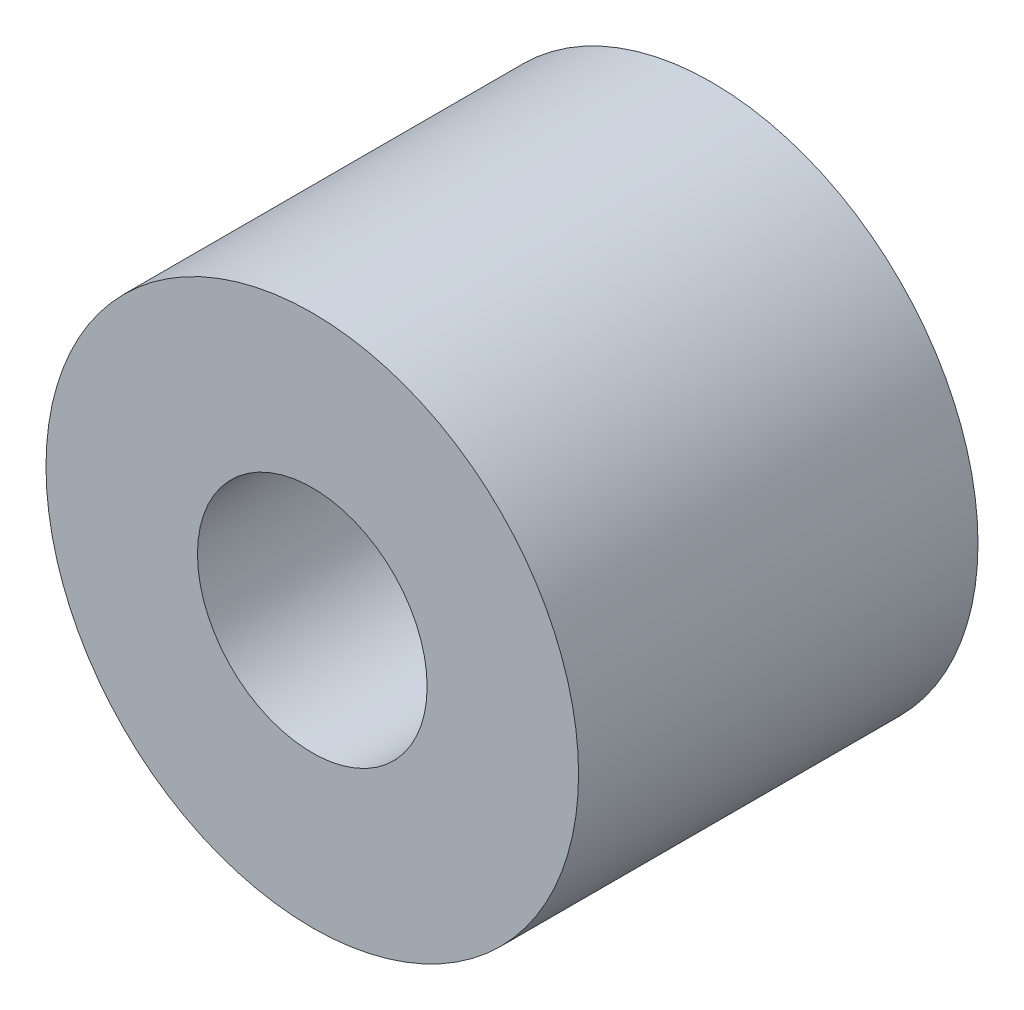
SolidWorks part; units mm, degrees
material "ABS"
ref_plane "Front Plane" through (0, 0, 0) normal (0, 0, 1) x (1, 0, 0)
ref_plane "Top Plane" through (0, 0, 0) normal (0, 1, 0) x (1, 0, 0)
ref_plane "Right Plane" through (0, 0, 0) normal (1, 0, 0) x (0, 0, -1)
sketch "Sketch1" plane through (0, 0, 0) normal (0, 0, 1) x (1, 0, 0)
  circle A0 centre (0, 0) radius 4
  circle A1 centre (0, 0) radius 1.725
  dimension "D1" = 3.45
  dimension "D2" = 8
extrude "Boss-Extrude1" add sketch "Sketch1" along normal blind 6
equation "\"D1@Sketch1\"=3+\"print_free@Parameters@FabricationParameters.sldprt\""
